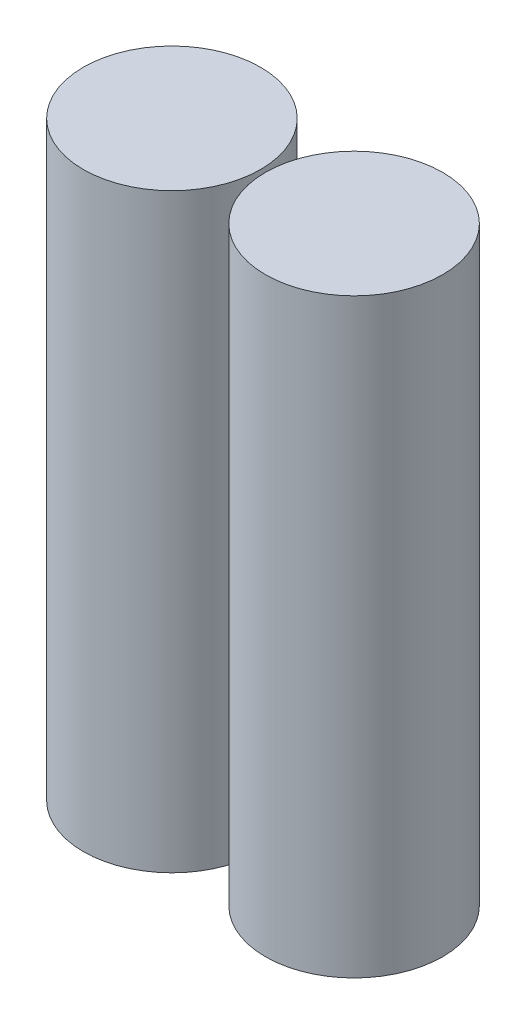
SolidWorks part; units mm, degrees
ref_plane "前视基准面" through (0, 0, 0) normal (0, 0, 1) x (1, 0, 0)
ref_plane "上视基准面" through (0, 0, 0) normal (0, 1, 0) x (1, 0, 0)
ref_plane "右视基准面" through (0, 0, 0) normal (1, 0, 0) x (0, 0, -1)
sketch "草图1" plane through (0, 0, 0) normal (0, 1, 0) x (1, 0, 0)
  circle A0 centre (0, 0) radius 9
  circle A2 centre (18.5, 0) radius 9
extrude "凸台-拉伸1" add sketch "草图1" along normal blind 60
